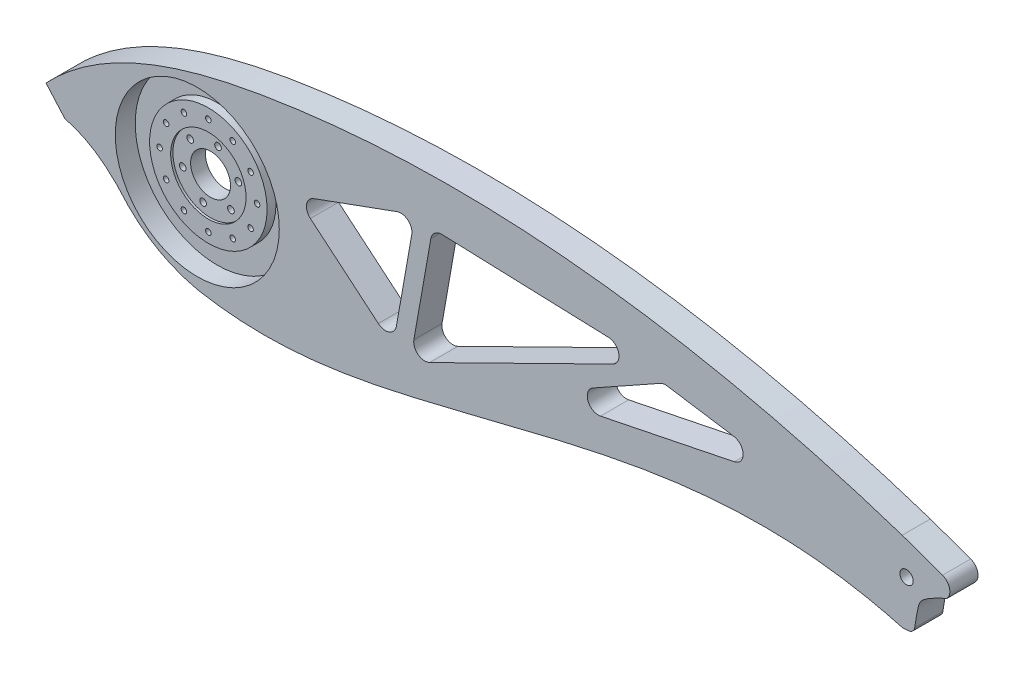
SolidWorks part; units mm, degrees
ref_plane "Front Plane" through (0, 0, 0) normal (0, 0, 1) x (1, 0, 0)
ref_plane "Top Plane" through (0, 0, 0) normal (0, 1, 0) x (1, 0, 0)
ref_plane "Right Plane" through (0, 0, 0) normal (1, 0, 0) x (0, 0, -1)
sketch "Croquis2" plane through (0, 0, 0) normal (0, 0, 1) x (1, 0, 0)
  line L3 (-68.2371, 4.5591) -> (-59.6532, -5.204)
  line L4 (318.0038, 21.0005) -> (336.1896, 14.479)
  arc A3 (338, 6.2) -> (336.1896, 14.479) centre (334.5018, 9.7725) ccw
  arc A4 (318.0038, -15.0543) -> (321.0712, -14.8533) centre (318.0038, 8.4457) ccw
  arc A5 (323.6438, -12.3415) -> (321.0712, -14.8533) centre (320.6796, -11.8789) cw
  spline S0 degree 3 poles (318.0038, 21.0005) (228.6128, 50.5792) (93.8377, 69.7133) (-40.8977, 33.4698) (-68.2371, 4.5591) knots 0 0 0 0 0.707437 1 1 1 1
  spline S2 degree 2 poles (0, -42) (-20.5144, -37.2835) (-33.9603, -21.8098) knots 0 0 0 1 1 1
  spline S3 degree 3 poles (0, -42) (34.8041, -48.5839) (140.6016, -28.663) (242.0663, 5.9793) (318.0038, -15.0543) knots 0 0 0 0 0.3223 1 1 1 1
  spline S4 degree 3 poles (338, 6.2) (337.9648, 6.1656) (334.3917, 4.9267) (325.4566, -0.139) (325.2312, -2.1702) (323.6438, -12.3415) knots 0.205944 0.205944 0.205944 0.205944 0.210384 0.5344 0.959977 0.959977 0.959977 0.959977
  spline S5 degree 3 poles (-31, -25) (-39.3963, -15.1385) (-48.3856, -7.8346) (-59.6532, -5.204) knots 0.532563 0.532563 0.532563 0.532563 1 1 1 1
  point P27 (53.7401, -43.3372)
  dimension "D1" = 5
  dimension "D2" = 3
  dimension "D3" = 13
extrude "Saliente-Extruir1" add sketch "Croquis2" along normal blind 12.7 contours S5 S2 S3 A4 A5 S4 A3 L4 S0 L3
sketch "Croquis5" plane through (0, 0, 12.7) normal (0, 0, 1) x (1, 0, 0)
  circle A0 centre (0, 0) radius 36
sketch "Croquis6" plane through (0, 0, 12.7) normal (0, 0, 1) x (1, 0, 0)
  circle A1 centre (0, 22) radius 1.25
  circle A2 centre (11, 19.0526) radius 1.25
  circle A3 centre (19.0526, 11) radius 1.25
  circle A4 centre (22, 0) radius 1.25
  circle A5 centre (19.0526, -11) radius 1.25
  circle A6 centre (11, -19.0526) radius 1.25
  circle A7 centre (0, -22) radius 1.25
  circle A8 centre (-11, -19.0526) radius 1.25
  circle A9 centre (-19.0526, -11) radius 1.25
  circle A10 centre (-22, 0) radius 1.25
  circle A11 centre (-19.0526, 11) radius 1.25
  circle A12 centre (-11, 19.0526) radius 1.25
  point P28 (0, 0)
  dimension "D1" = 12
sketch "Croquis8" plane through (0, 0, 12.7) normal (0, 0, 1) x (1, 0, 0)
  circle A0 centre (319.9513, 5.5848) radius 3
sketch "Croquis12" plane through (0, 0, 0) normal (0, 0, -1) x (-1, 0, 0)
  circle A0 centre (0, 0) radius 17
  circle A1 centre (0, 0) radius 26
sketch "Croquis13" plane through (0, 0, 0) normal (0, 0, -1) x (-1, 0, 0)
  circle A6 centre (12.557, -3.3646) radius 1.5
  circle A7 centre (3.3646, -12.557) radius 1.5
  circle A8 centre (-9.1924, -9.1924) radius 1.5
  circle A10 centre (9.1924, 9.1924) radius 1.5
  circle A11 centre (-12.557, 3.3646) radius 1.5
  circle A12 centre (-3.3646, 12.557) radius 1.5
  point P14 (0, 0)
  point P15 (0, 0)
  dimension "D1" = 6
sketch "Croquis15" plane through (0, 0, 12.7) normal (0, 0, 1) x (1, 0, 0)
  line L0 (97.7235, -12.7568) -> (105.3612, 30.5587)
  line L1 (110.4597, 34.6874) -> (185.414, 32.07)
  line L2 (89.8227, -11.4945) -> (96.7686, 27.8978)
  line L3 (90.1344, 33.4645) -> (52.5467, 19.7837)
  line L4 (51.0429, 11.255) -> (81.6847, -14.4565)
  line L5 (187.4496, 22.588) -> (104.8576, -18.1101)
  line L6 (178.4856, 8.7617) -> (208.7865, 25.7186)
  line L7 (211.9904, 26.297) -> (242.0099, 21.667)
  line L8 (242.2488, 11.8267) -> (181.9285, -0.5003)
  circle A0 centre (77, 11.075) radius 10 construction
  arc A1 (89.8227, -11.4945) -> (81.6847, -14.4565) centre (84.8986, -10.6263) cw
  arc A2 (52.5467, 19.7837) -> (51.0429, 11.255) centre (54.2568, 15.0852) ccw
  arc A3 (96.7686, 27.8978) -> (90.1344, 33.4645) centre (91.8445, 28.766) ccw
  arc A4 (97.7235, -12.7568) -> (104.8576, -18.1101) centre (102.6475, -13.625) ccw
  arc A5 (105.3612, 30.5587) -> (110.4597, 34.6874) centre (110.2852, 29.6905) cw
  arc A6 (185.414, 32.07) -> (187.4496, 22.588) centre (185.2395, 27.073) cw
  arc A7 (178.4856, 8.7617) -> (181.9285, -0.5003) centre (180.9274, 4.3985) ccw
  arc A8 (242.0099, 21.667) -> (242.2488, 11.8267) centre (241.2477, 16.7254) cw
  arc A9 (208.7865, 25.7186) -> (211.9904, 26.297) centre (211.2282, 21.3554) cw
  dimension "D1" = 5
  dimension "D2" = 5
  dimension "D3" = 5
  dimension "D4" = 3
  dimension "D5" = 8
extrude "Cortar-Extruir20" cut sketch "Croquis15" against normal blind 62
extrude "Cortar-Extruir21" cut sketch "Croquis12" against normal blind 4
extrude "Cortar-Extruir22" cut sketch "Croquis6" against normal blind 29
extrude "Cortar-Extruir23" cut sketch "Croquis13" against normal blind 29 contours A12 | A10 | A6 | A7 | A8 | A11
extrude "Cortar-Extruir27" cut sketch "Croquis8" against normal blind 64 contours A0
extrude "Cortar-Extruir28" cut sketch "Croquis5" against normal blind 4 contours A0
sketch "Croquis22" plane through (0, 0, 8.7) normal (0, 0, 1) x (1, 0, 0)
  circle A0 centre (0, 0) radius 27
extrude "Cortar-Extruir32" cut sketch "Croquis22" against normal blind 1
sketch "Croquis23" plane through (0, 0, 7.7) normal (0, 0, 1) x (1, 0, 0)
  circle A0 centre (0, 0) radius 17
extrude "Cortar-Extruir33" cut sketch "Croquis23" against normal blind 1
sketch "Croquis24" plane through (0, 0, 0) normal (0, 0, -1) x (-1, 0, 0)
  circle A0 centre (0, 0) radius 9
extrude "Cortar-Extruir34" cut sketch "Croquis24" against normal blind 67
sketch "Croquis26" plane through (0, 0, 12.7) normal (0, 0, 1) x (1, 0, 0)
  circle A0 centre (0, 0) radius 37
  circle A1 centre (0, 0) radius 26.5
extrude "Cortar-Extruir38" cut sketch "Croquis26" against normal blind 9 contours A0 | A1
